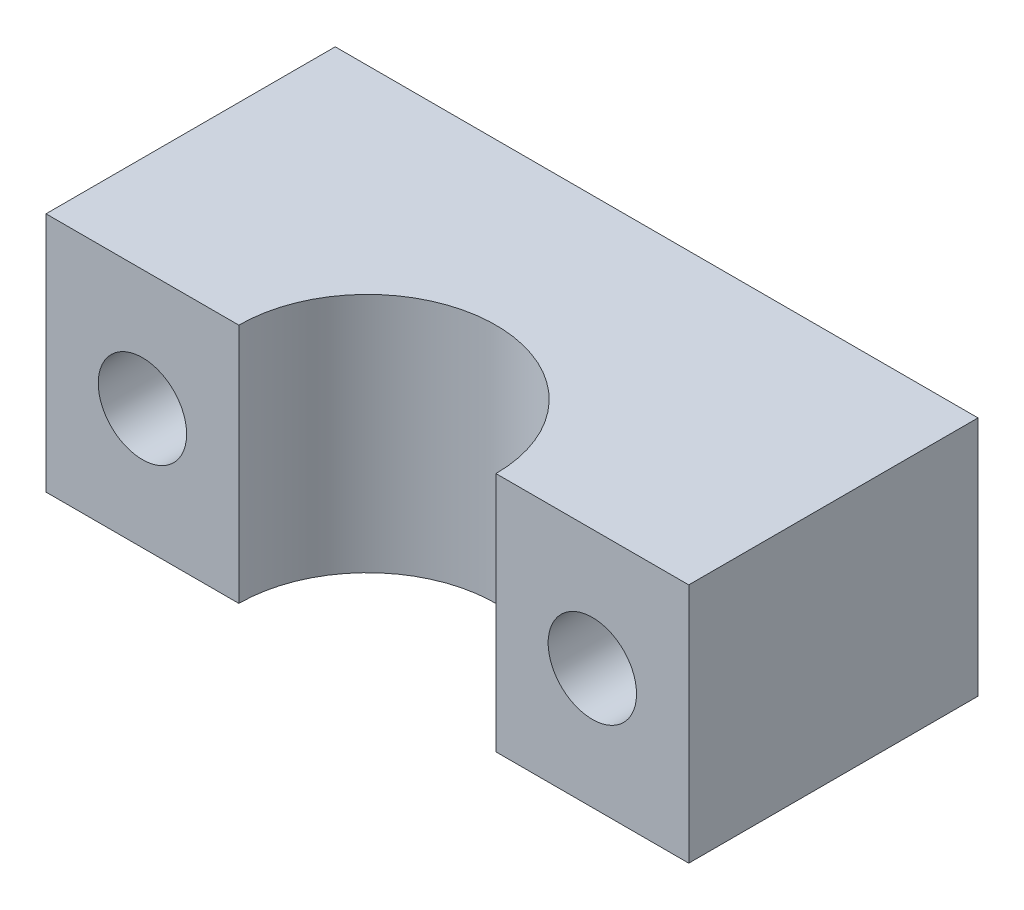
SolidWorks part; units mm, degrees
ref_plane "前视基准面" through (0, 0, 0) normal (0, 0, 1) x (1, 0, 0)
ref_plane "上视基准面" through (0, 0, 0) normal (0, 1, 0) x (1, 0, 0)
ref_plane "右视基准面" through (0, 0, 0) normal (1, 0, 0) x (0, 0, -1)
sketch "草图1" plane through (0, 0, 0) normal (0, 0, 1) x (1, 0, 0)
  line L1 (0, 0) -> (40, 0)
  line L2 (0, 0) -> (0, -15)
  line L3 (0, -15) -> (40, -15)
  line L4 (40, 0) -> (40, -15)
  dimension "D1" = 15
  dimension "D2" = 40
extrude "凸台-拉伸1" add sketch "草图1" along normal blind 18
sketch "草图2" plane through (0, 0, 0) normal (0, 1, 0) x (1, 0, 0)
  line L0 (40, -18) -> (0, -18) construction
  circle A0 centre (20, -18) radius 8
  dimension "D1" = 16
extrude "切除-拉伸1" cut sketch "草图2" against normal blind 15
sketch "草图4" plane through (0, 0, 18) normal (0, 0, 1) x (1, 0, 0)
  line L0 (12, 0) -> (0, 0) construction
  line L1 (40, 0) -> (28, 0) construction
  line L3 (28, 0) -> (12, 0) construction
  circle A0 centre (34, -7.5) radius 2.75
  circle A1 centre (6, -7.5) radius 2.75
  point P13 (20, 0)
  dimension "D1" = 5.5
  dimension "D2" = 5.5
  dimension "D3" = 28
  dimension "D4" = 7.5
  dimension "D5" = 7.5
  dimension "D6" = 14
extrude "切除-拉伸2" cut sketch "草图4" against normal through all
